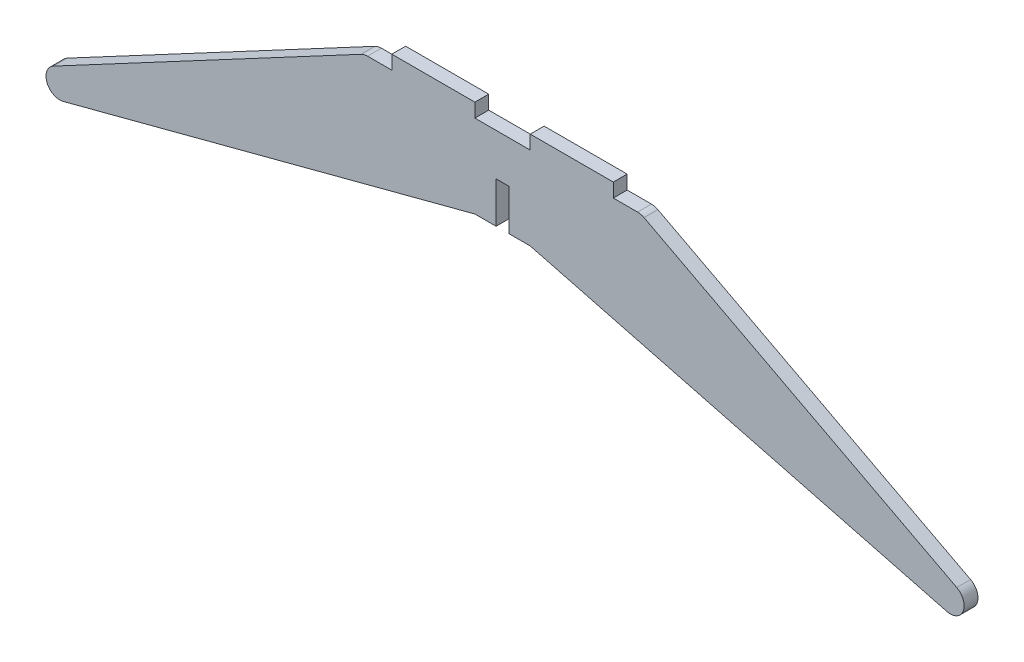
SolidWorks part; units mm, degrees
material "Teak"
ref_plane "Front Plane" through (0, 0, 0) normal (0, 0, 1) x (1, 0, 0)
ref_plane "Top Plane" through (0, 0, 0) normal (0, 1, 0) x (1, 0, 0)
ref_plane "Right Plane" through (0, 0, 0) normal (1, 0, 0) x (0, 0, -1)
sketch "Sketch1" plane through (0, 0, 0) normal (0, 0, 1) x (1, 0, 0)
  line L0 (25.4, 0) -> (30.968, 0)
  line L1 (-6.35, 0) -> (6.35, 0)
  line L2 (-30.9562, 0) -> (-25.4, 0)
  line L3 (1.4859, -19.05) -> (1.4859, -9.6266)
  line L4 (-1.4859, -19.05) -> (-1.4859, -9.6266)
  line L5 (-1.4859, -9.6266) -> (1.4859, -9.6266)
  line L6 (-6.35, -19.05) -> (-1.4859, -19.05)
  line L7 (1.4859, -19.05) -> (6.35, -19.05)
  line L8 (6.35, -19.05) -> (101.8924, -43.8589)
  line L9 (104.1649, -37.9739) -> (32.4425, -0.3632)
  line L10 (-32.4504, -0.3735) -> (-103.0239, -38.0127)
  line L11 (-100.7218, -43.8847) -> (-6.35, -19.05)
  line L12 (-6.35, 3.175) -> (-25.4, 3.175)
  line L13 (-25.4, 0) -> (-25.4, 3.175)
  line L14 (-6.35, 3.175) -> (-6.35, 0)
  line L15 (25.4, 3.175) -> (6.35, 3.175)
  line L16 (6.35, 0) -> (6.35, 3.175)
  line L17 (25.4, 3.175) -> (25.4, 0)
  arc A0 (101.8924, -43.8589) -> (104.1649, -37.9739) centre (102.6904, -40.7858) ccw
  arc A1 (32.4425, -0.3632) -> (30.968, 0) centre (30.968, -3.175) ccw
  arc A2 (-30.9562, 0) -> (-32.4504, -0.3735) centre (-30.9562, -3.175) ccw
  arc A3 (-103.0239, -38.0127) -> (-100.7218, -43.8847) centre (-101.5298, -40.8142) ccw
  point P27 (-6.35, 0)
  point P30 (25.4, 0)
extrude "Boss-Extrude1" add sketch "Sketch1" along normal blind 3.175
